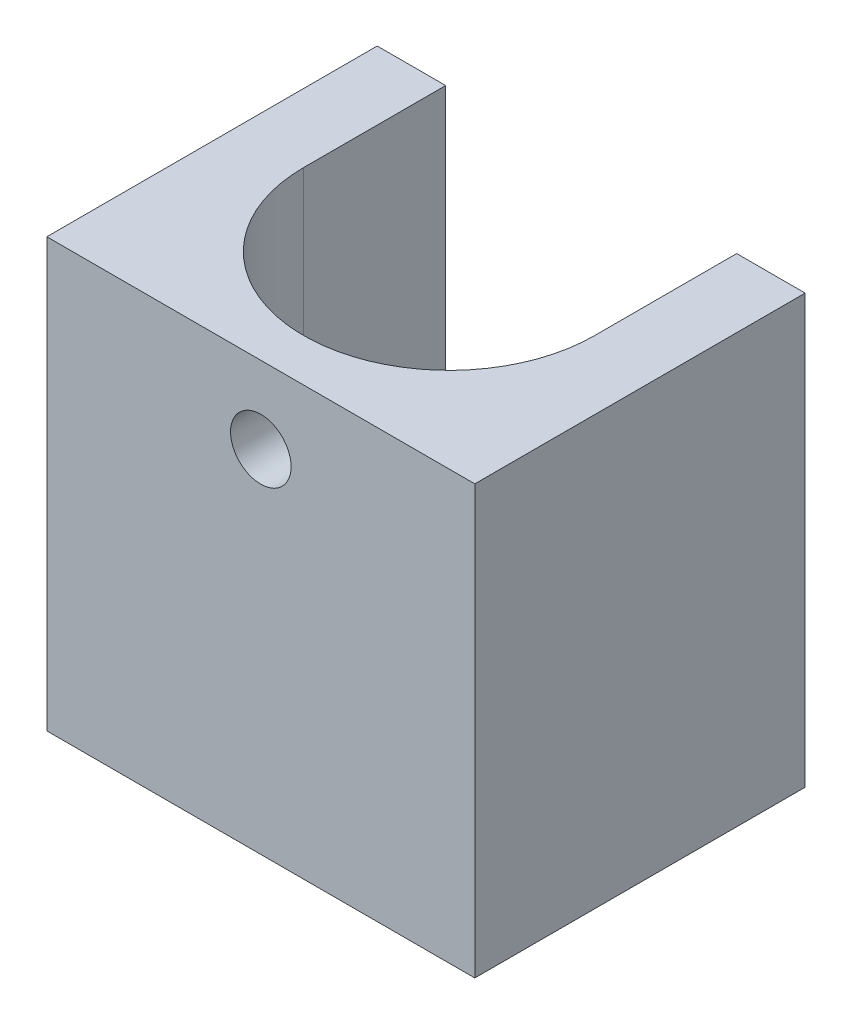
SolidWorks part; units mm, degrees
ref_plane "Front Plane" through (0, 0, 0) normal (0, 0, 1) x (1, 0, 0)
ref_plane "Top Plane" through (0, 0, 0) normal (0, 1, 0) x (1, 0, 0)
ref_plane "Right Plane" through (0, 0, 0) normal (1, 0, 0) x (0, 0, -1)
sketch "Sketch1" plane through (0, 0, 0) normal (0, 1, 0) x (1, 0, 0)
  line L1 (-15.875, -1.5875) -> (15.875, -1.5875)
  line L2 (-15.875, -1.5875) -> (-15.875, 1.5875)
  line L3 (-15.875, 1.5875) -> (15.875, 1.5875)
  line L4 (15.875, -1.5875) -> (15.875, 1.5875)
  line L5 (-15.875, -1.5875) -> (15.875, 1.5875) construction
  line L6 (-15.875, 1.5875) -> (15.875, -1.5875) construction
  point P0 (0, 0)
  dimension "D1" = 3.175
  dimension "D2" = 31.75
extrude "Boss-Extrude1" add sketch "Sketch1" along normal blind 31.75
sketch "Sketch2" plane through (0, 31.75, 0) normal (0, 1, 0) x (1, 0, 0)
  line L0 (15.875, -1.5875) -> (15.875, 1.5875) construction
  line L1 (15.875, 1.5875) -> (-15.875, 1.5875) construction
  line L2 (-15.875, 1.5875) -> (-15.875, 12.3825)
  line L3 (-10.795, 12.3825) -> (-15.875, 12.3825)
  line L4 (-15.875, 1.5875) -> (0, 1.5875)
  arc A0 (-10.795, 12.3825) -> (0, 1.5875) centre (0, 12.3825) ccw
  dimension "D2" = 21.59
  dimension "D1" = 15.875
extrude "Boss-Extrude2" add sketch "Sketch2" against normal blind 31.75
mirror "Mirror1" about plane through (0, 0, 0) normal (1, 0, 0) of "Boss-Extrude2"
sketch "Sketch3" plane through (0, 31.75, 0) normal (0, 1, 0) x (1, 0, 0)
  line L0 (-15.875, 12.3825) -> (-10.795, 12.3825)
  line L1 (-10.795, 12.3825) -> (-10.795, 22.9235)
  line L2 (-10.795, 22.9235) -> (-15.875, 22.9235)
  line L3 (-15.875, 22.9235) -> (-15.875, 12.3825)
  dimension "D1" = 10.541
extrude "Boss-Extrude3" add sketch "Sketch3" against normal blind 31.75
mirror "Mirror2" about plane through (0, 0, 0) normal (1, 0, 0) of "Boss-Extrude3"
sketch "Sketch4" plane through (0, 0, 1.5875) normal (0, 0, 1) x (1, 0, 0)
  line L0 (0, 0) -> (0, 31.75) construction
  line L1 (-15.875, 31.75) -> (15.875, 31.75) construction
  line L2 (5.204, 28.0912) -> (5.204, 26.035) construction
  line L3 (5.204, 26.035) -> (6.8861, 26.035) construction
  line L4 (5.204, 28.0912) -> (7.4117, 28.0912) construction
  circle A0 centre (0, 26.035) radius 2.2463
  circle A1 centre (0, 5.715) radius 2.1193
  point P7 (0, 15.875)
  dimension "D1" = 4.4926
  dimension "D4" = 4.2386
  dimension "D2" = 10.16
  dimension "D3" = 20.32
extrude "Cut-Extrude1" cut sketch "Sketch4" against normal blind 31.75
sketch "Sketch6" plane through (0, 0, 1.5875) normal (0, 0, 1) x (1, 0, 0)
  circle A0 centre (0, 5.715) radius 2.1193 construction
  circle A1 centre (0, 5.715) radius 2.1193
extrude "Boss-Extrude4" add sketch "Sketch6" against normal blind 15.875
fillet "Fillet1" radius 0.762 1 edges at (2.1193, 5.715, -14.2875)
